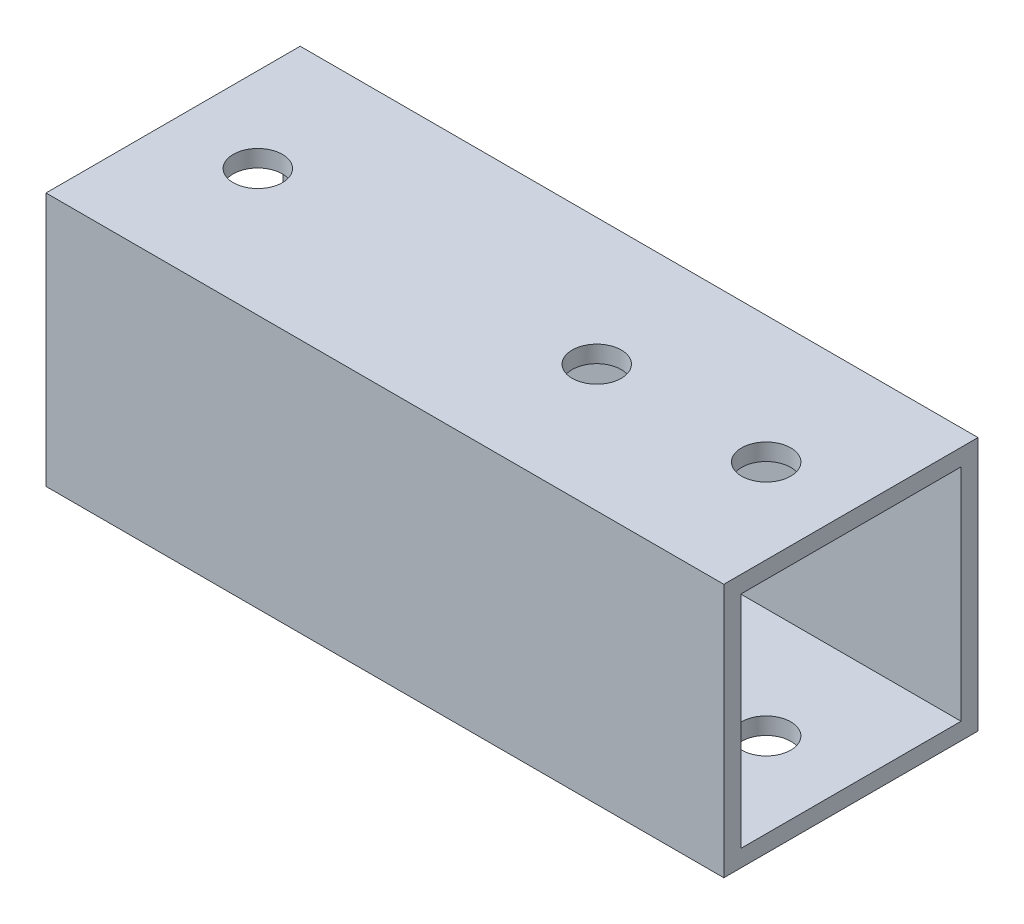
SolidWorks part; units mm, degrees
material "Thornel Mat VMA"
ref_plane "前视基准面" through (0, 0, 0) normal (0, 0, 1) x (1, 0, 0)
ref_plane "上视基准面" through (0, 0, 0) normal (0, 1, 0) x (1, 0, 0)
ref_plane "右视基准面" through (0, 0, 0) normal (1, 0, 0) x (0, 0, -1)
other "Configuration Table"
sketch "草图1" plane through (0, 0, 0) normal (1, 0, 0) x (0, 0, -1)
  line L0 (-6.5, -6.5) -> (-6.5, 6.5)
  line L1 (-7.5, -7.5) -> (7.5, -7.5)
  line L2 (-7.5, -7.5) -> (-7.5, 7.5)
  line L3 (-7.5, 7.5) -> (7.5, 7.5)
  line L4 (7.5, -7.5) -> (7.5, 7.5)
  line L5 (-7.5, -7.5) -> (7.5, 7.5) construction
  line L6 (-7.5, 7.5) -> (7.5, -7.5) construction
  line L7 (-6.5, 6.5) -> (6.5, 6.5)
  line L8 (6.5, -6.5) -> (6.5, 6.5)
  line L9 (-6.5, -6.5) -> (6.5, -6.5)
  point P0 (0, 0)
  dimension "D1" = 15
  dimension "D2" = 15
  dimension "D3" = 1
extrude "凸台-拉伸1" add sketch "草图1" along normal blind 40
sketch "草图2" plane through (0, 7.5, 0) normal (0, 1, 0) x (1, 0, 0)
  circle A0 centre (5, 0) radius 1.45 construction
  circle A1 centre (25, 0) radius 1.45 construction
  circle A2 centre (35, 0) radius 1.45 construction
  circle A3 centre (5, 0) radius 1.45
  circle A4 centre (25, 0) radius 1.45
  circle A5 centre (35, 0) radius 1.45
extrude "切除-拉伸1" cut sketch "草图2" against normal through all
